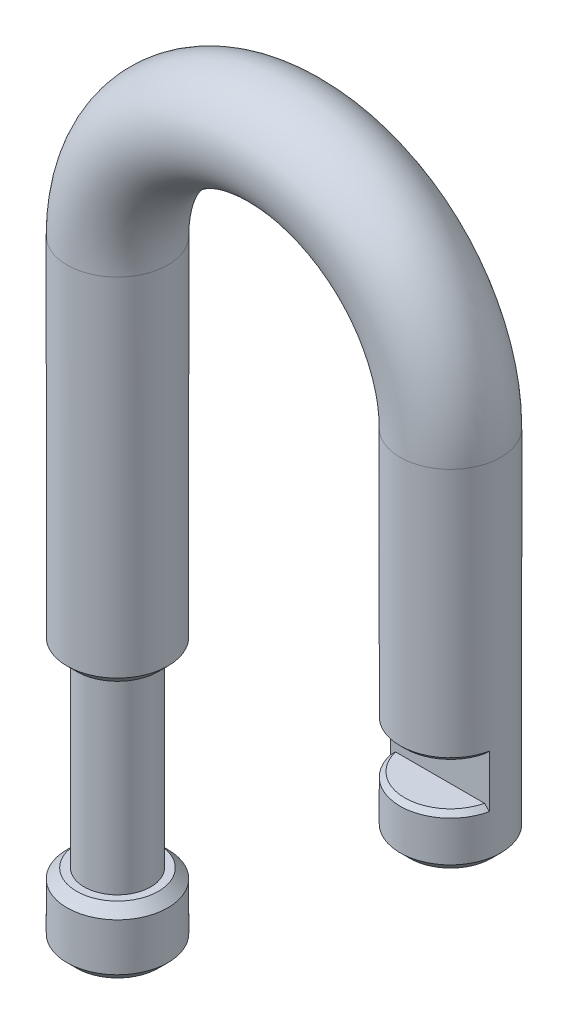
SolidWorks part; units mm, degrees
ref_plane "Front Plane" through (0, 0, 0) normal (0, 0, 1) x (1, 0, 0)
ref_plane "Top Plane" through (0, 0, 0) normal (0, 1, 0) x (1, 0, 0)
ref_plane "Right Plane" through (0, 0, 0) normal (1, 0, 0) x (0, 0, -1)
sketch "Sketch1" plane through (0, 0, 0) normal (0, 0, 1) x (1, 0, 0)
  line L0 (0, 0) -> (0, 64.5)
  line L1 (0, 64.5) -> (35, 64.5) construction
  line L2 (35, 64.5) -> (35, 27.5)
  arc A0 (0, 64.5) -> (35, 64.5) centre (17.5, 64.5) cw
  dimension "D1" = 35
  dimension "D2" = 64.5
  dimension "D3" = 37
sketch "Sketch2" plane through (0, 0, 0) normal (0, 1, 0) x (1, 0, 0)
  circle A0 centre (0, 0) radius 5.3
  dimension "D1" = 10.6
sweep "Sweep1" add profiles "Sketch2" path "Sketch1"
sketch "Sketch4" plane through (0, 27.5, 0) normal (0, -1, 0) x (1, 0, 0)
  line L0 (29.8154, 1.1) -> (40.1846, 1.1)
  line L1 (35, -5.3) -> (35, 5.3) construction
  circle A0 centre (35, 0) radius 5.3 construction
  circle A1 centre (35, 0) radius 5.3 construction
  circle A2 centre (35, 0) radius 5.475
  circle M3 centre (35, 0) radius 5.3
  dimension "D2" = 10.95
  dimension "D1" = 4.2
extrude "Cut-Extrude1" cut sketch "Sketch4" against normal blind 4.5 from offset 5.75 contours L0 L1 A2 | L1 L0 M3 offset against normal yes
sketch "Sketch6" plane through (0, 0, 0) normal (0, -1, 0) x (1, 0, 0)
  circle A0 centre (0, 0) radius 5.475
  circle A1 centre (0, 0) radius 3.5
  dimension "D1" = 10.95
  dimension "D2" = 7
extrude "Cut-Extrude2" cut sketch "Sketch6" against normal blind 20 from offset 7 offset against normal yes
sketch "Dimention" plane through (0, 0, 0) normal (0, 0, 1) x (1, 0, 0)
  line L0 (0, 0) -> (0, 33.25) construction
  line L1 (0, 33.25) -> (35, 33.25) construction
  line L2 (40.1846, 33.25) -> (29.8154, 33.25) construction
  line L3 (35, 33.25) -> (35, 27.5) construction
  line L4 (29.7, 27.5) -> (40.3, 27.5) construction
  line L5 (0, 7) -> (0, 27) construction
  line L6 (5.3, 7) -> (-5.3, 7) construction
  line L7 (-3.5, 27) -> (3.5, 27) construction
  line L8 (29.8154, 37.75) -> (40.1846, 37.75) construction
  dimension "D1" = 33.25
  dimension "D2" = 35
  dimension "D3" = 5.75
  dimension "D4" = 20
  dimension "D5" = 7
  dimension "D6" = 4.5
chamfer "Chamfer1" distance 1 angle 45 4 edges at (35, 27.5, 5.3) (0, 0, 5.3) (0, 7, -5.3) (0, 27, -5.3)
chamfer "Chamfer2" distance 0.5 angle 45 2 edges at (35, 37.75, 5.3) (35, 33.25, 5.3)
